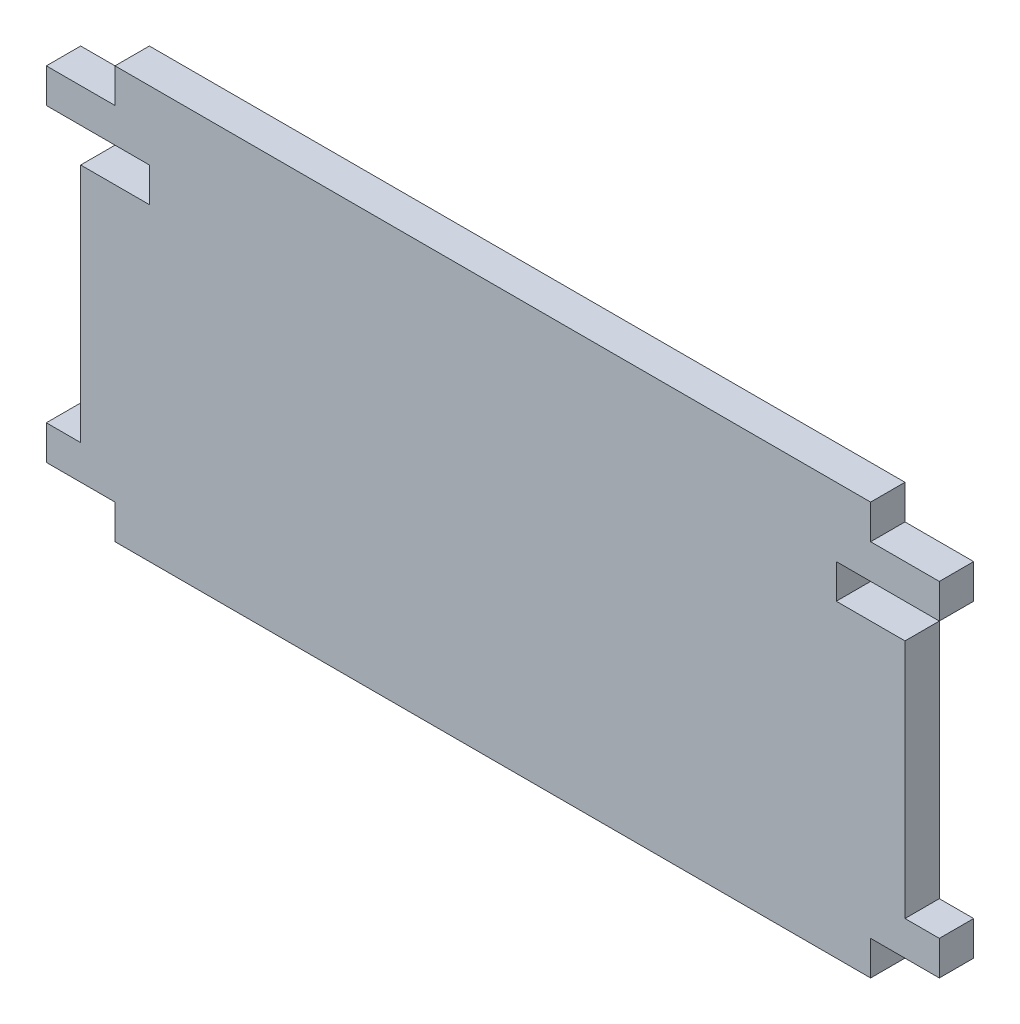
SolidWorks part; units mm, degrees
ref_plane "Front Plane" through (0, 0, 0) normal (0, 0, 1) x (1, 0, 0)
ref_plane "Top Plane" through (0, 0, 0) normal (0, 1, 0) x (1, 0, 0)
ref_plane "Right Plane" through (0, 0, 0) normal (1, 0, 0) x (0, 0, -1)
sketch "Sketch1" plane through (0, 0, 0) normal (0, 0, 1) x (1, 0, 0)
  line L0 (107.95, 3.175) -> (107.95, 9.525)
  line L1 (107.95, 9.525) -> (101.6, 9.525)
  line L2 (101.6, 9.525) -> (101.6, 60.325)
  line L3 (101.6, 60.325) -> (107.95, 60.325)
  line L4 (107.95, 60.325) -> (107.95, 66.675)
  line L5 (107.95, 66.675) -> (95.25, 66.675)
  line L6 (95.25, 66.675) -> (95.25, 73.025)
  line L7 (95.25, 73.025) -> (-44.45, 73.025)
  line L8 (-44.45, 73.025) -> (-44.45, 66.675)
  line L9 (-44.45, 66.675) -> (-57.15, 66.675)
  line L10 (-57.15, 66.675) -> (-57.15, 60.325)
  line L11 (-57.15, 60.325) -> (-50.8, 60.325)
  line L12 (-50.8, 60.325) -> (-50.8, 9.525)
  line L13 (-50.8, 9.525) -> (-57.15, 9.525)
  line L14 (-57.15, 9.525) -> (-57.15, 3.175)
  line L15 (-57.15, 3.175) -> (-44.45, 3.175)
  line L16 (-44.45, 3.175) -> (-44.45, -3.175)
  line L17 (-44.45, -3.175) -> (95.25, -3.175)
  line L18 (95.25, -3.175) -> (95.25, 3.175)
  line L19 (95.25, 3.175) -> (107.95, 3.175)
  line L20 (107.95, 73.025) -> (101.6, 73.025) construction
  dimension "D1" = 6.35
extrude "Boss-Extrude1" add sketch "Sketch1" against normal up to surface (6.35 mm away)
sketch "Sketch2" plane through (0, 0, 0) normal (0, 0, 1) x (1, 0, 0)
  line L4 (107.95, 60.325) -> (88.9, 60.325)
  line L5 (88.9, 60.325) -> (88.9, 53.975)
  line L6 (88.9, 53.975) -> (107.95, 53.975)
  line L7 (107.95, 53.975) -> (107.95, 60.325)
  line L8 (107.95, 60.325) -> (88.9, 60.325)
  line L9 (88.9, 60.325) -> (88.9, 53.975)
  line L10 (88.9, 53.975) -> (107.95, 53.975)
  line L11 (107.95, 53.975) -> (107.95, 60.325)
  line L12 (-38.1, 60.325) -> (-57.15, 60.325)
  line L13 (-57.15, 60.325) -> (-57.15, 53.975)
  line L14 (-57.15, 53.975) -> (-38.1, 53.975)
  line L15 (-38.1, 53.975) -> (-38.1, 60.325)
  line L16 (-38.1, 60.325) -> (-57.15, 60.325)
  line L17 (-57.15, 60.325) -> (-57.15, 53.975)
  line L18 (-57.15, 53.975) -> (-38.1, 53.975)
  line L19 (-38.1, 53.975) -> (-38.1, 60.325)
  dimension "D1" = 0
  dimension "D2" = 0
extrude "Cut-Extrude1" cut sketch "Sketch2" against normal through all
